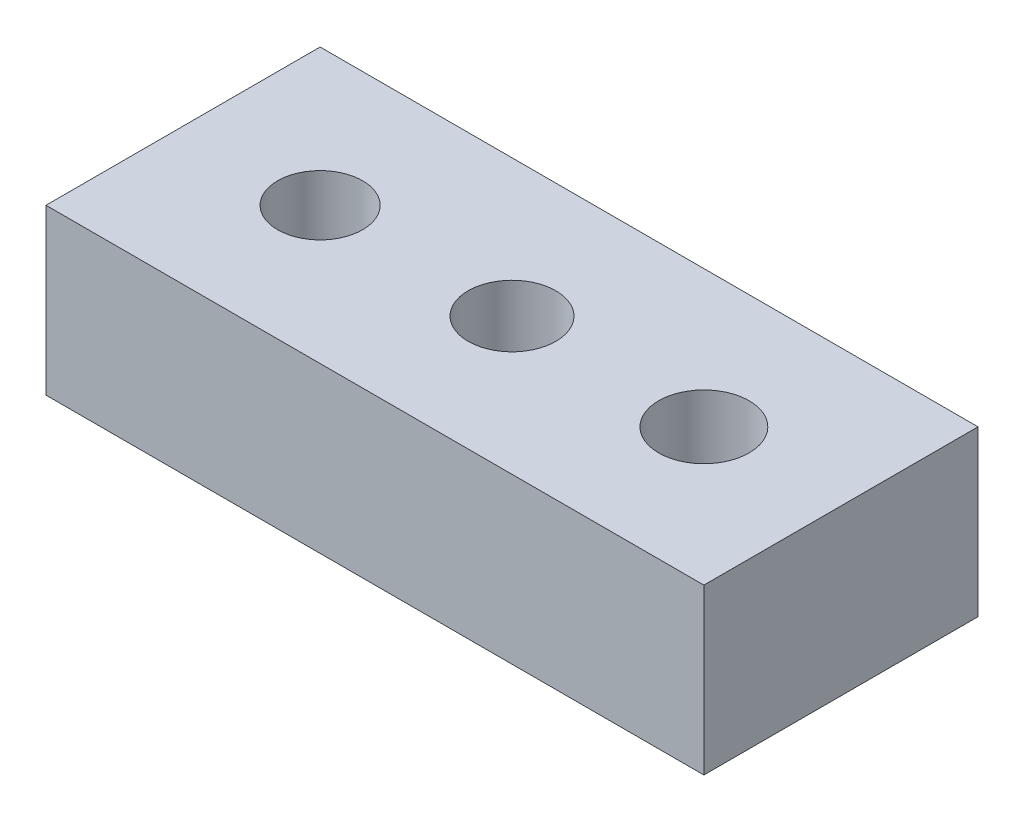
SolidWorks part; units mm, degrees
ref_plane "前视基准面" through (0, 0, 0) normal (0, 0, 1) x (1, 0, 0)
ref_plane "上视基准面" through (0, 0, 0) normal (0, 1, 0) x (1, 0, 0)
ref_plane "右视基准面" through (0, 0, 0) normal (1, 0, 0) x (0, 0, -1)
other "Configuration Table"
sketch "草图1" plane through (0, 0, 0) normal (0, 1, 0) x (1, 0, 0)
  line L0 (-14.9708, 5) -> (17.2078, 5) construction
  line L1 (0, 0) -> (24, 0)
  line L2 (0, 0) -> (0, 10)
  line L3 (0, 10) -> (24, 10)
  line L4 (24, 0) -> (24, 10)
  circle A0 centre (5, 5) radius 1.55
  circle A1 centre (12, 5) radius 1.6
  circle A2 centre (19, 5) radius 1.65
  dimension "D2" = 3.1
  dimension "D3" = 3.2
  dimension "D4" = 3.3
  dimension "D1" = 10
  dimension "D5" = 7
  dimension "D6" = 7
  dimension "D7" = 5
  dimension "D8" = 5
extrude "凸台-拉伸1" add sketch "草图1" along normal blind 6
